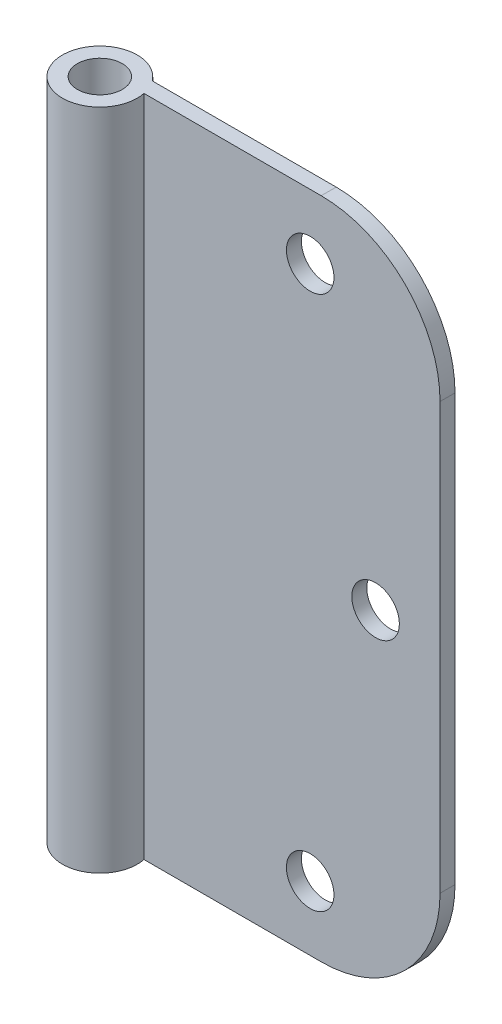
SolidWorks part; units mm, degrees
ref_plane "Plan de face" through (0, 0, 0) normal (0, 0, 1) x (1, 0, 0)
ref_plane "Plan de dessus" through (0, 0, 0) normal (0, 1, 0) x (1, 0, 0)
ref_plane "Plan de droite" through (0, 0, 0) normal (1, 0, 0) x (0, 0, -1)
sketch "Esquisse1" plane through (0, 0, 0) normal (0, 0, 1) x (1, 0, 0)
  line L0 (44.45, 0) -> (44.45, -88.646) construction
  line L1 (49.45, 0) -> (88.9, 0)
  line L2 (0, -44.323) -> (0, -88.646) construction
  line L3 (49.45, -88.646) -> (88.9, -88.646)
  line L4 (88.9, 0) -> (88.9, -88.646)
  line L5 (88.9, -44.323) -> (0, -44.323) construction
  line L6 (0, 0) -> (44.45, 0) construction
  line L7 (0, 0) -> (0, -44.323) construction
  line L8 (0, -88.646) -> (44.45, -88.646) construction
  line L9 (49.45, 0) -> (49.45, -88.646)
  line L10 (44.45, 0) -> (49.45, 0) construction
  line L11 (44.45, -88.646) -> (49.45, -88.646) construction
  circle A0 centre (80.2894, -44.323) radius 3.175
  circle A1 centre (71.5518, -8.61) radius 3.175
  circle A2 centre (71.5518, -80.036) radius 3.175
  dimension "D3" = 6.35
  dimension "D4" = 8.6106
  dimension "D5" = 6.35
  dimension "D6" = 8.61
  dimension "D7" = 17.3482
  dimension "D1" = 88.9
  dimension "D2" = 88.646
  dimension "D8" = 44.45
  dimension "D9" = 5
extrude "Boss.-Extru.1" add sketch "Esquisse1" along normal blind 2
sketch "Esquisse2" plane through (0, 0, 2) normal (0, 0, 1) x (1, 0, 0)
  line L0 (69.175, 0) -> (69.175, -88.646)
  line L1 (88.9, 0) -> (49.45, 0) construction
  line L2 (49.45, -88.646) -> (88.9, -88.646) construction
fillet "Congé1" radius 15.875 2 edges at (88.9, -88.646, 1) (88.9, 0, 1)
sketch "Esquisse3" plane through (0, 0, 0) normal (0, 1, 0) x (1, 0, 0)
  line L0 (73.025, 0) -> (49.45, 0) construction
  line L1 (49.45, -2) -> (49.45, 0) construction
  line L2 (49.45, 0) -> (48.45, 0)
  line L3 (49.45, -2) -> (49.349, -2)
  line L4 (49.45, 0) -> (49.45, -2)
  arc A0 (48.45, 0) -> (49.349, -2) centre (44.45, -3) ccw
  arc A1 (49.349, -2) -> (48.45, 0) centre (44.45, -3) ccw construction
  circle A2 centre (44.45, -3) radius 3
  dimension "D1" = 10
  dimension "D4" = 6
  dimension "D2" = 3
  dimension "D3" = 5
extrude "Boss.-Extru.2" add sketch "Esquisse3" against normal up to surface (88.646 mm away) up to face at (61.2375, -88.646, 1)
